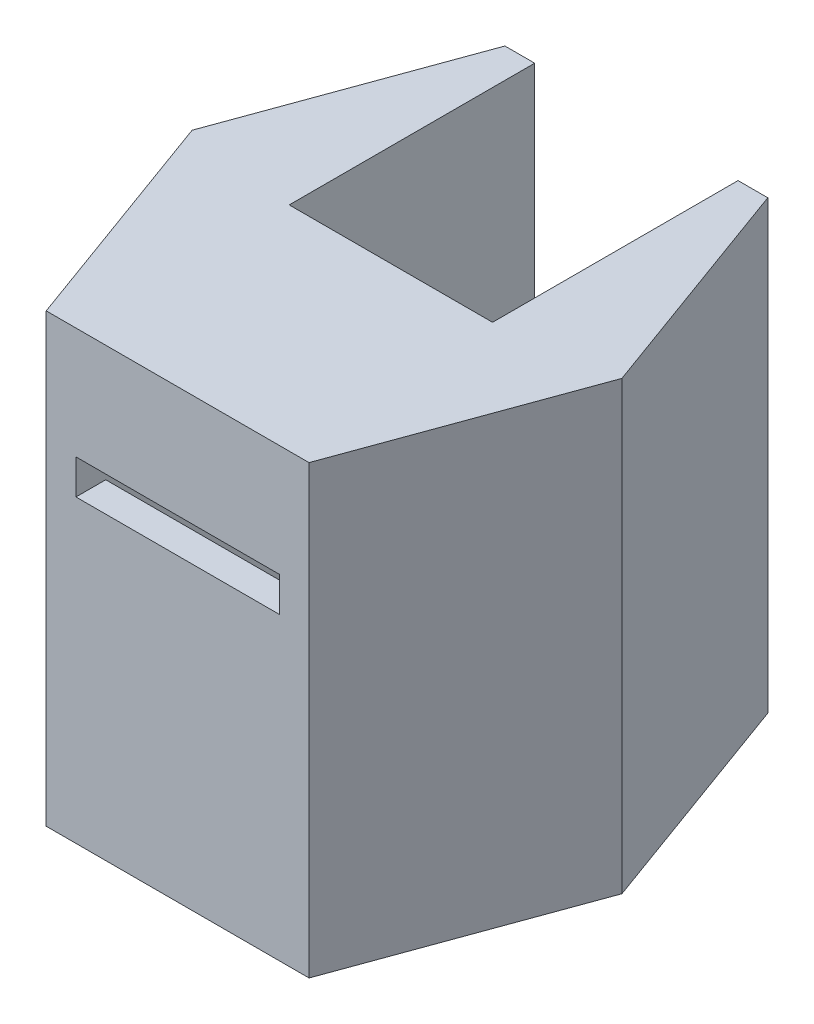
SolidWorks part; units mm, degrees
ref_plane "Front Plane" through (0, 0, 0) normal (0, 0, 1) x (1, 0, 0)
ref_plane "Top Plane" through (0, 0, 0) normal (0, 1, 0) x (1, 0, 0)
ref_plane "Right Plane" through (0, 0, 0) normal (1, 0, 0) x (0, 0, -1)
sketch "Sketch1" plane through (0, 0, 0) normal (0, 1, 0) x (1, 0, 0)
  line L0 (0, 0) -> (26.5, 0)
  line L1 (26.5, 0) -> (34.9168, 23.125)
  line L2 (34.9168, 23.125) -> (26.5, 46.25)
  line L4 (0, 46.25) -> (-8.4168, 23.125)
  line L5 (-8.4168, 23.125) -> (0, 0)
  line L6 (0, 46.25) -> (3, 46.25)
  line L7 (3, 46.25) -> (3, 3)
  line L8 (3, 3) -> (23.5, 3)
  line L9 (23.5, 3) -> (23.5, 46.25)
  line L10 (23.5, 46.25) -> (26.5, 46.25)
  dimension "D1" = 26.5
  dimension "D2" = 3
  dimension "D3" = 140
  dimension "D4" = 140
  dimension "D5" = 46.25
  dimension "D6" = 20.5
  dimension "D7" = 3
extrude "Boss-Extrude1" add sketch "Sketch1" along normal blind 45
sketch "Sketch2" plane through (0, 0, -3) normal (0, 0, -1) x (-1, 0, 0)
  line L0 (-23.5, 45) -> (-3, 45)
  line L1 (-3, 45) -> (-3, 43)
  line L2 (-3, 45) -> (-3, 0) construction
  line L3 (-3, 43) -> (-23.5, 43)
  line L4 (-23.5, 45) -> (-23.5, 0) construction
  line L5 (-23.5, 43) -> (-23.5, 45)
  dimension "D1" = 2
extrude "Boss-Extrude2" add sketch "Sketch2" along normal blind 18.5
sketch "Sketch3" plane through (0, 0, -3) normal (0, 0, -1) x (-1, 0, 0)
  line L0 (-23.5, 33.75) -> (-3, 33.75)
  line L1 (-23.5, 45) -> (-23.5, 0) construction
  line L2 (-3, 43) -> (-3, 0) construction
  line L3 (-3, 33.75) -> (-3, 30.25)
  line L4 (-3, 45) -> (-3, 0) construction
  line L5 (-3, 30.25) -> (-23.5, 30.25)
  line L6 (-23.5, 43) -> (-23.5, 0) construction
  line L7 (-23.5, 30.25) -> (-23.5, 33.75)
  line L8 (-23.5, 43) -> (-3, 43) construction
  dimension "D1" = 3.5
  dimension "D2" = 9.25
extrude "Cut-Extrude1" cut sketch "Sketch3" against normal blind 20
sketch "Sketch4" plane through (0, 0, -3) normal (0, 0, -1) x (-1, 0, 0)
  line L0 (-23.5, 0) -> (-23.5, 3)
  line L1 (-23.5, 45) -> (-23.5, 0) construction
  line L2 (-23.5, 3) -> (-3, 3)
  line L3 (-3, 30.25) -> (-3, 0) construction
  line L4 (-3, 3) -> (-3, 0)
  line L5 (-3, 0) -> (-23.5, 0)
  dimension "D1" = 3
extrude "Boss-Extrude3" add sketch "Sketch4" along normal up to surface (43.25 mm away) up to face at (25, 22.5, -46.25)
